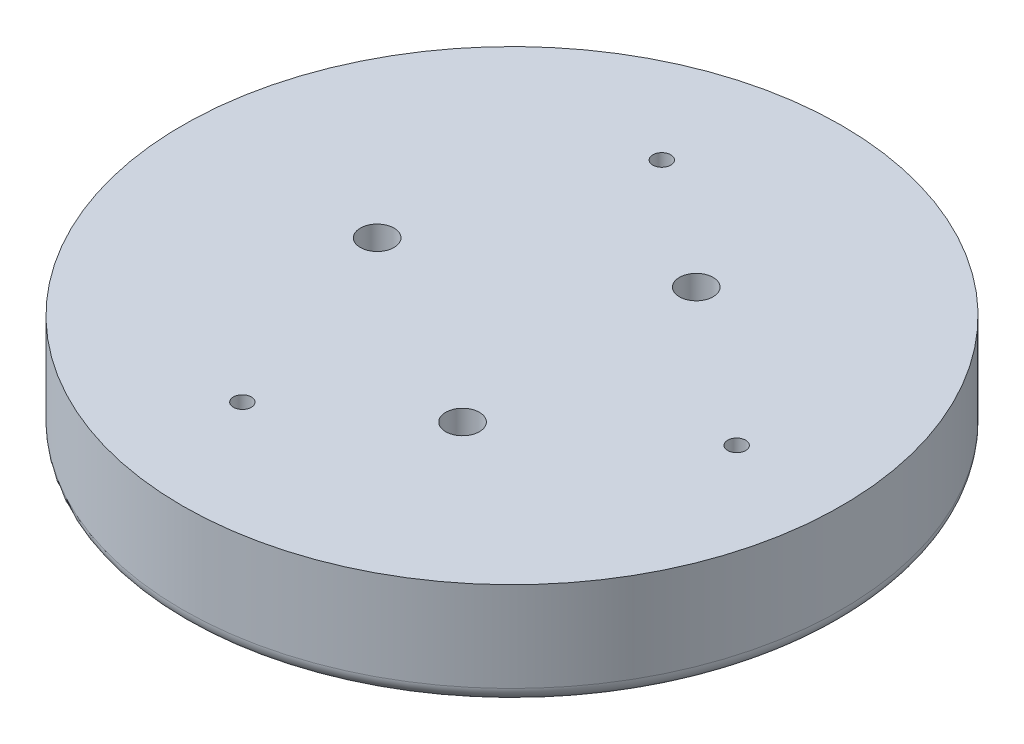
SolidWorks part; units mm, degrees
ref_plane "Спереди" through (0, 0, 0) normal (0, 0, 1) x (1, 0, 0)
ref_plane "Сверху" through (0, 0, 0) normal (0, 1, 0) x (1, 0, 0)
ref_plane "Справа" through (0, 0, 0) normal (1, 0, 0) x (0, 0, -1)
sketch "Sketch1" plane through (0, 0, 0) normal (0, 1, 0) x (1, 0, 0)
  line L0 (-11.7247, 0) -> (16.8046, 0) construction
  line L1 (0, 7.3106) -> (0, -15.7423) construction
  circle A0 centre (0, 0) radius 22
  circle A1 centre (-4, 14) radius 0.6
  circle A2 centre (-4, -14) radius 0.6
  circle A3 centre (15, 0) radius 0.6
  circle A4 centre (-9, 0) radius 1.125
  circle A5 centre (4.5, 7.8) radius 1.125
  circle A6 centre (4.5, -7.8) radius 1.125
  dimension "D1" = 44
  dimension "D7" = 1.2
  dimension "D8" = 1.2
  dimension "D9" = 1.2
  dimension "D10" = 2.25
  dimension "D11" = 2.25
  dimension "D12" = 2.25
  dimension "D2" = 15
  dimension "D3" = 4
  dimension "D4" = 14
  dimension "D5" = 14
  dimension "D6" = 4
  dimension "D13" = 9
  dimension "D14" = 4.5
  dimension "D15" = 7.8
  dimension "D16" = 7.8
  dimension "D17" = 4.5
extrude "Boss-Extrude1" add sketch "Sketch1" along normal blind 7
fillet "Fillet1" radius 1 1 edges at (0, 0, 22)
